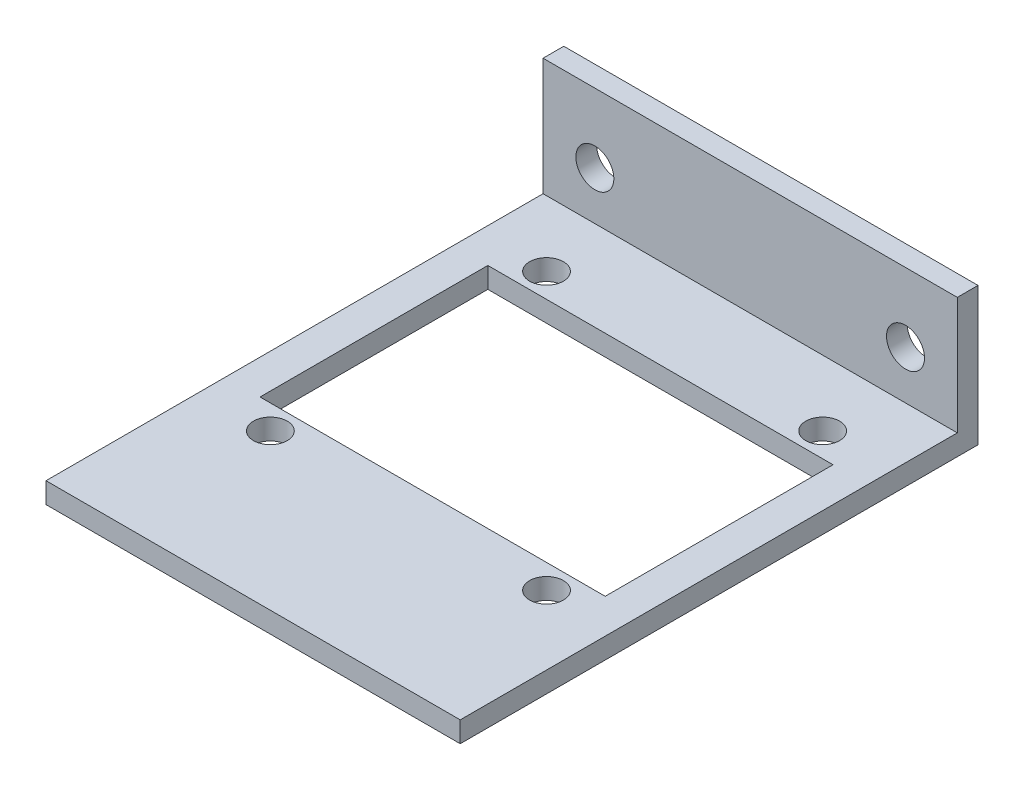
SolidWorks part; units mm, degrees
ref_plane "Front Plane" through (0, 0, 0) normal (0, 0, 1) x (1, 0, 0)
ref_plane "Top Plane" through (0, 0, 0) normal (0, 1, 0) x (1, 0, 0)
ref_plane "Right Plane" through (0, 0, 0) normal (1, 0, 0) x (0, 0, -1)
sketch "Sketch1" plane through (0, 0, 0) normal (0, 1, 0) x (1, 0, 0)
  line L1 (-30, -37.5) -> (30, -37.5)
  line L2 (-30, -37.5) -> (-30, 37.5)
  line L3 (-30, 37.5) -> (30, 37.5)
  line L4 (30, -37.5) -> (30, 37.5)
  line L5 (-30, -37.5) -> (30, 37.5) construction
  line L6 (-30, 37.5) -> (30, -37.5) construction
  point P0 (0, 0)
  dimension "D1" = 75
  dimension "D2" = 60
extrude "Boss-Extrude1" add sketch "Sketch1" along normal blind 3 contours L2 L3 L4 L1
sketch "Sketch2" plane through (0, 3, 0) normal (0, 1, 0) x (1, 0, 0)
  line L0 (30, -37.5) -> (30, 37.5) construction
  line L1 (-30, 37.5) -> (30, 37.5)
  line L2 (-30, 37.5) -> (-30, 34.5)
  line L3 (-30, 34.5) -> (30, 34.5)
  line L4 (30, 37.5) -> (30, 34.5)
  dimension "D1" = 3
extrude "Boss-Extrude2" add sketch "Sketch2" along normal offset from surface (17 mm away) 20 up to face at (0, 0, 0)
sketch "Sketch3" plane through (0, 3, 0) normal (0, 1, 0) x (1, 0, 0)
  line L0 (-11, 0) -> (11, 0) construction
  line L1 (-25, 21.5) -> (25, 21.5)
  line L2 (-25, 21.5) -> (-25, -11.5)
  line L3 (-25, -11.5) -> (25, -11.5)
  line L4 (25, 21.5) -> (25, -11.5)
  line L5 (-25, 21.5) -> (25, -11.5) construction
  line L6 (-25, -11.5) -> (25, 21.5) construction
  point P0 (0, 5)
  point P6 (0, 0)
  dimension "D1" = 50
  dimension "D2" = 33
  dimension "D3" = 5
extrude "Cut-Extrude1" cut sketch "Sketch3" against normal up to next
sketch "Sketch4" plane through (0, 3, 0) normal (0, 1, 0) x (1, 0, 0)
  line L0 (25, -11.5) -> (25, 21.5) construction
  line L1 (-20, 25) -> (20, 25) construction
  line L2 (-20, 25) -> (-20, -15) construction
  line L3 (-20, -15) -> (20, -15) construction
  line L4 (20, 25) -> (20, -15) construction
  line L5 (-20, 25) -> (20, -15) construction
  line L6 (-20, -15) -> (20, 25) construction
  circle A0 centre (-20, 25) radius 2.45
  circle A1 centre (20, 25) radius 2.45
  circle A2 centre (20, -15) radius 2.45
  circle A3 centre (-20, -15) radius 2.45
  point P0 (0, 5)
  point P10 (0, 0)
  point P11 (20, 5)
  point P14 (25, 5)
  dimension "D2" = 4.9
  dimension "D1" = 40
extrude "Cut-Extrude2" cut sketch "Sketch4" against normal up to next
sketch "Sketch6" plane through (0, 0, -37.5) normal (0, 0, -1) x (-1, 0, 0)
  line L0 (0, 20) -> (0, 0) construction
  line L1 (-30, 20) -> (30, 20) construction
  line L2 (-22.5, 10) -> (22.5, 10) construction
  line L3 (30, 20) -> (30, 0) construction
  point P8 (0, 10)
  dimension "D1" = 7.5
hole_wizard "M5 Clearance Hole1" positions "3DSketch1" profile "Sketch7" hole size "M5" standard "ANSI Metric" end condition through all
sketch3d "3DSketch1"
  point P0 (22.5, 10, -37.5)
  point P3 (-22.5, 10, -37.5)
sketch "Sketch7" plane through (22.5, 10, -37.5) normal (1, 0, 0) x (0, 1, 0)
  line L0 (0, 0) -> (0, 75)
  line L1 (0, 75) -> (2.75, 75)
  line L2 (2.75, 75) -> (2.75, 0)
  line L5 (2.75, 0) -> (0, 0)
  line L11 (0, -6.35) -> (0, 107.95) construction
  dimension "Thru Hole Dia." = 5.5
  dimension "Thru Hole Depth" = 75
